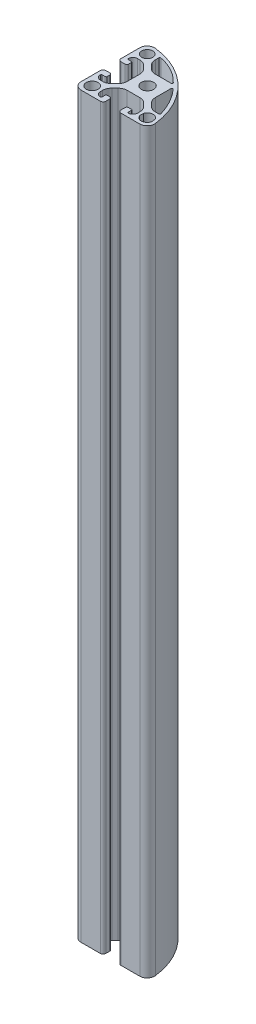
SolidWorks part; units mm, degrees
ref_plane "Alzado" through (0, 0, 0) normal (0, 0, 1) x (1, 0, 0)
ref_plane "Planta" through (0, 0, 0) normal (0, 1, 0) x (1, 0, 0)
ref_plane "Vista lateral" through (0, 0, 0) normal (1, 0, 0) x (0, 0, -1)
sketch "Croquis1" plane through (0, 0, 0) normal (0, 1, 0) x (1, 0, 0)
  line L0 (-18.2, 12.3) -> (-18.2, 15.7771)
  line L1 (-12.3, 11.8) -> (-17.7, 11.8)
  line L2 (-11.8, 16.9053) -> (-11.8, 12.3)
  line L3 (11.8, -17.7) -> (11.8, -12.3)
  line L4 (15.7771, -18.2) -> (12.3, -18.2)
  line L5 (12.3, -11.8) -> (16.9053, -11.8)
  line L6 (-18.2, -16) -> (-18.2, -12.3)
  line L7 (-12.3, -18.2) -> (-16, -18.2)
  line L8 (-11.8, -12.3) -> (-11.8, -17.7)
  line L9 (-17.7, -11.8) -> (-12.3, -11.8)
  line L10 (-10.1, 14.2924) -> (-10.1, 16.2371)
  line L11 (-6.9431, 9.0645) -> (-8.6355, 10.7569)
  line L12 (5.1332, 7.6) -> (-3.4076, 7.6)
  line L13 (4.1, -16.35) -> (4.1, -18.5)
  line L14 (5.6, -20) -> (15.7771, -20)
  line L15 (-20, 15.7771) -> (-20, 5.6)
  line L16 (-18.5, 4.1) -> (-16.35, 4.1)
  line L17 (-15.35, 5.1) -> (-15.35, 6.6)
  line L18 (-15.85, 7.1) -> (-17.5, 7.1)
  line L19 (-15.5, 10.1) -> (-14.2924, 10.1)
  line L20 (-10.7569, 8.6355) -> (-9.0645, 6.9431)
  line L21 (-7.6, 3.4076) -> (-7.6, -3.4076)
  line L22 (-9.0645, -6.9431) -> (-10.7569, -8.6355)
  line L23 (-14.2924, -10.1) -> (-15.5, -10.1)
  line L24 (-17.5, -7.1) -> (-15.85, -7.1)
  line L25 (-15.35, -6.6) -> (-15.35, -5.1)
  line L26 (-16.35, -4.1) -> (-18.5, -4.1)
  line L27 (-20, -5.6) -> (-20, -16)
  line L28 (-16, -20) -> (-5.6, -20)
  line L29 (-4.1, -18.5) -> (-4.1, -16.35)
  line L30 (-5.1, -15.35) -> (-6.6, -15.35)
  line L31 (-7.1, -15.85) -> (-7.1, -17.5)
  line L32 (-10.1, -15.5) -> (-10.1, -14.2924)
  line L33 (-8.6355, -10.7569) -> (-6.9431, -9.0645)
  line L34 (-3.4076, -7.6) -> (3.4076, -7.6)
  line L35 (6.9431, -9.0645) -> (8.6355, -10.7569)
  line L36 (10.1, -14.2924) -> (10.1, -15.5)
  line L37 (7.1, -17.5) -> (7.1, -15.85)
  line L38 (6.6, -15.35) -> (5.1, -15.35)
  line L39 (16.2371, -10.1) -> (14.2924, -10.1)
  line L40 (10.7569, -8.6355) -> (9.0645, -6.9431)
  line L41 (7.6, -3.4076) -> (7.6, 5.1332)
  circle A0 centre (0, 0) radius 3.35
  arc A1 (-15.7556, 17.9635) -> (-18.2, 15.7771) centre (-16, 15.7771) ccw
  arc A2 (-18.2, 12.3) -> (-17.7, 11.8) centre (-17.7, 12.3) ccw
  arc A3 (-12.3, 11.8) -> (-11.8, 12.3) centre (-12.3, 12.3) ccw
  arc A4 (-11.8, 16.9053) -> (-12.1979, 17.3947) centre (-12.3, 16.9053) ccw
  arc A5 (-12.1979, 17.3947) -> (-15.7556, 17.9635) centre (-20, -20) ccw
  arc A6 (12.3, -11.8) -> (11.8, -12.3) centre (12.3, -12.3) ccw
  arc A7 (11.8, -17.7) -> (12.3, -18.2) centre (12.3, -17.7) ccw
  arc A8 (15.7771, -18.2) -> (17.9635, -15.7556) centre (15.7771, -16) ccw
  arc A9 (17.9635, -15.7556) -> (17.3947, -12.1979) centre (-20, -20) ccw
  arc A10 (17.3947, -12.1979) -> (16.9053, -11.8) centre (16.9053, -12.3) ccw
  arc A11 (-17.7, -11.8) -> (-18.2, -12.3) centre (-17.7, -12.3) ccw
  arc A12 (-18.2, -16) -> (-16, -18.2) centre (-16, -16) ccw
  arc A13 (-12.3, -18.2) -> (-11.8, -17.7) centre (-12.3, -17.7) ccw
  arc A14 (-11.8, -12.3) -> (-12.3, -11.8) centre (-12.3, -12.3) ccw
  arc A15 (4.1, -18.5) -> (5.6, -20) centre (5.6, -18.5) ccw
  arc A16 (15.7771, -20) -> (19.7523, -15.5556) centre (15.7771, -16) ccw
  arc A17 (19.7523, -15.5556) -> (-15.5556, 19.7523) centre (-20, -20) ccw
  arc A18 (-15.5556, 19.7523) -> (-20, 15.7771) centre (-16, 15.7771) ccw
  arc A19 (-20, 5.6) -> (-18.5, 4.1) centre (-18.5, 5.6) ccw
  arc A20 (-16.35, 4.1) -> (-15.35, 5.1) centre (-16.35, 5.1) ccw
  arc A21 (-15.35, 6.6) -> (-15.85, 7.1) centre (-15.85, 6.6) ccw
  arc A22 (-18, 7.6) -> (-17.5, 7.1) centre (-17.5, 7.6) ccw
  arc A23 (-15.5, 10.1) -> (-18, 7.6) centre (-15.5, 7.6) ccw
  arc A24 (-10.7569, 8.6355) -> (-14.2924, 10.1) centre (-14.2924, 5.1) ccw
  arc A25 (-7.6, 3.4076) -> (-9.0645, 6.9431) centre (-12.6, 3.4076) ccw
  arc A26 (-9.0645, -6.9431) -> (-7.6, -3.4076) centre (-12.6, -3.4076) ccw
  arc A27 (-14.2924, -10.1) -> (-10.7569, -8.6355) centre (-14.2924, -5.1) ccw
  arc A28 (-18, -7.6) -> (-15.5, -10.1) centre (-15.5, -7.6) ccw
  arc A29 (-17.5, -7.1) -> (-18, -7.6) centre (-17.5, -7.6) ccw
  arc A30 (-15.85, -7.1) -> (-15.35, -6.6) centre (-15.85, -6.6) ccw
  arc A31 (-15.35, -5.1) -> (-16.35, -4.1) centre (-16.35, -5.1) ccw
  arc A32 (-18.5, -4.1) -> (-20, -5.6) centre (-18.5, -5.6) ccw
  arc A33 (-20, -16) -> (-16, -20) centre (-16, -16) ccw
  arc A34 (-5.6, -20) -> (-4.1, -18.5) centre (-5.6, -18.5) ccw
  arc A35 (-4.1, -16.35) -> (-5.1, -15.35) centre (-5.1, -16.35) ccw
  arc A36 (-6.6, -15.35) -> (-7.1, -15.85) centre (-6.6, -15.85) ccw
  arc A37 (-7.6, -18) -> (-7.1, -17.5) centre (-7.6, -17.5) ccw
  arc A38 (-10.1, -15.5) -> (-7.6, -18) centre (-7.6, -15.5) ccw
  arc A39 (-8.6355, -10.7569) -> (-10.1, -14.2924) centre (-5.1, -14.2924) ccw
  arc A40 (-3.4076, -7.6) -> (-6.9431, -9.0645) centre (-3.4076, -12.6) ccw
  arc A41 (6.9431, -9.0645) -> (3.4076, -7.6) centre (3.4076, -12.6) ccw
  arc A42 (10.1, -14.2924) -> (8.6355, -10.7569) centre (5.1, -14.2924) ccw
  arc A43 (7.6, -18) -> (10.1, -15.5) centre (7.6, -15.5) ccw
  arc A44 (7.1, -17.5) -> (7.6, -18) centre (7.6, -17.5) ccw
  arc A45 (7.1, -15.85) -> (6.6, -15.35) centre (6.6, -15.85) ccw
  arc A46 (5.1, -15.35) -> (4.1, -16.35) centre (5.1, -16.35) ccw
  arc A47 (-9.4621, 16.7177) -> (-10.1, 16.2371) centre (-9.6, 16.2371) ccw
  arc A48 (-10.1, 14.2924) -> (-8.6355, 10.7569) centre (-5.1, 14.2924) ccw
  arc A49 (-6.9431, 9.0645) -> (-3.4076, 7.6) centre (-3.4076, 12.6) ccw
  arc A50 (5.1332, 7.6) -> (5.4666, 8.4727) centre (5.1332, 8.1) ccw
  arc A51 (16.7177, -9.4621) -> (8.4727, 5.4666) centre (-20, -20) ccw
  arc A52 (16.2371, -10.1) -> (16.7177, -9.4621) centre (16.2371, -9.6) ccw
  arc A53 (10.7569, -8.6355) -> (14.2924, -10.1) centre (14.2924, -5.1) ccw
  arc A54 (7.6, -3.4076) -> (9.0645, -6.9431) centre (12.6, -3.4076) ccw
  arc A55 (8.4727, 5.4666) -> (7.6, 5.1332) centre (8.1, 5.1332) ccw
  arc A56 (-9.4621, 16.7177) -> (5.4666, 8.4727) centre (-14.5044, -10.0495) cw
extrude "Saliente-Extruir1" add sketch "Croquis1" along normal blind 400
sketch "Croquis2" plane through (0, 400, 0) normal (0, 1, 0) x (1, 0, 0)
  line L0 (-18.2, 15.7771) -> (-18.2, 12.3) construction
  line L1 (-17.7, 11.8) -> (-12.3, 11.8) construction
  line L2 (-11.8, 12.3) -> (-11.8, 16.9053) construction
  line L3 (-18.2, 15.7771) -> (-18.2, 12.3)
  line L4 (-17.7, 11.8) -> (-12.3, 11.8)
  line L5 (-11.8, 12.3) -> (-11.8, 16.9053)
  line L6 (-16, -18.2) -> (-12.3, -18.2) construction
  line L7 (-18.2, -12.3) -> (-18.2, -16) construction
  line L8 (-12.3, -11.8) -> (-17.7, -11.8) construction
  line L9 (-11.8, -17.7) -> (-11.8, -12.3) construction
  line L10 (-16, -18.2) -> (-12.3, -18.2)
  line L11 (-18.2, -12.3) -> (-18.2, -16)
  line L12 (-12.3, -11.8) -> (-17.7, -11.8)
  line L13 (-11.8, -17.7) -> (-11.8, -12.3)
  line L14 (12.3, -18.2) -> (15.7771, -18.2) construction
  line L15 (11.8, -12.3) -> (11.8, -17.7) construction
  line L16 (16.9053, -11.8) -> (12.3, -11.8) construction
  line L17 (12.3, -18.2) -> (15.7771, -18.2)
  line L18 (11.8, -12.3) -> (11.8, -13.9666)
  line L19 (16.9053, -11.8) -> (12.3, -11.8)
  line L20 (11.8, -16.0334) -> (11.8, -17.7)
  arc A0 (-11.8, 16.9053) -> (-12.1979, 17.3947) centre (-12.3, 16.9053) ccw construction
  arc A1 (-12.1979, 17.3947) -> (-15.7556, 17.9635) centre (-20, -20) ccw construction
  arc A2 (-15.7556, 17.9635) -> (-18.2, 15.7771) centre (-16, 15.7771) ccw construction
  arc A3 (-18.2, 12.3) -> (-17.7, 11.8) centre (-17.7, 12.3) ccw construction
  arc A4 (-12.3, 11.8) -> (-11.8, 12.3) centre (-12.3, 12.3) ccw construction
  arc A5 (-11.8, 16.9053) -> (-12.1979, 17.3947) centre (-12.3, 16.9053) ccw
  arc A6 (-12.1979, 17.3947) -> (-15.7556, 17.9635) centre (-20, -20) ccw
  arc A7 (-15.7556, 17.9635) -> (-18.2, 15.7771) centre (-16, 15.7771) ccw
  arc A8 (-18.2, 12.3) -> (-17.7, 11.8) centre (-17.7, 12.3) ccw
  arc A9 (-12.3, 11.8) -> (-11.8, 12.3) centre (-12.3, 12.3) ccw
  arc A10 (-12.3, -18.2) -> (-11.8, -17.7) centre (-12.3, -17.7) ccw construction
  arc A11 (-18.2, -16) -> (-16, -18.2) centre (-16, -16) ccw construction
  arc A12 (-17.7, -11.8) -> (-18.2, -12.3) centre (-17.7, -12.3) ccw construction
  arc A13 (-11.8, -12.3) -> (-12.3, -11.8) centre (-12.3, -12.3) ccw construction
  arc A14 (-12.3, -18.2) -> (-11.8, -17.7) centre (-12.3, -17.7) ccw
  arc A15 (-18.2, -16) -> (-16, -18.2) centre (-16, -16) ccw
  arc A16 (-17.7, -11.8) -> (-18.2, -12.3) centre (-17.7, -12.3) ccw
  arc A17 (-11.8, -12.3) -> (-12.3, -11.8) centre (-12.3, -12.3) ccw
  arc A18 (17.3947, -12.1979) -> (16.9053, -11.8) centre (16.9053, -12.3) ccw construction
  arc A19 (17.9635, -15.7556) -> (17.3947, -12.1979) centre (-20, -20) ccw construction
  arc A20 (15.7771, -18.2) -> (17.9635, -15.7556) centre (15.7771, -16) ccw construction
  arc A21 (11.8, -17.7) -> (12.3, -18.2) centre (12.3, -17.7) ccw construction
  arc A22 (12.3, -11.8) -> (11.8, -12.3) centre (12.3, -12.3) ccw construction
  arc A23 (17.3947, -12.1979) -> (16.9053, -11.8) centre (16.9053, -12.3) ccw
  arc A24 (17.9635, -15.7556) -> (17.9551, -15.6816) centre (-20, -20) ccw
  arc A25 (15.7771, -18.2) -> (17.9635, -15.7556) centre (15.7771, -16) ccw
  arc A26 (11.8, -17.7) -> (12.3, -18.2) centre (12.3, -17.7) ccw
  arc A27 (12.3, -11.8) -> (11.8, -12.3) centre (12.3, -12.3) ccw
  circle A28 centre (-14.9928, 14.8209) radius 3.0209
  circle A29 centre (-15, -15) radius 3.2
  circle A30 centre (14.8285, -15) radius 3.2
  arc A31 (17.6371, -13.4664) -> (17.3947, -12.1979) centre (-20, -20) ccw
extrude "Saliente-Extruir2" add sketch "Croquis2" against normal up to surface (400 mm away) contours A29 L13 A17 L12 | A29 L10 A14 L13 | A29 L11 A15 L10 | A29 L12 A16 L11 | A28 A6 A7 L3 A8 L4 | A28 L4 A9 L5 A5 A6 | A30 A31 A23 L19 | A30 L19 A27 L18 | A30 L20 A26 L17 | A30 L17 A25 A24 up to face at (-4.7129, 0, -11.4358)
